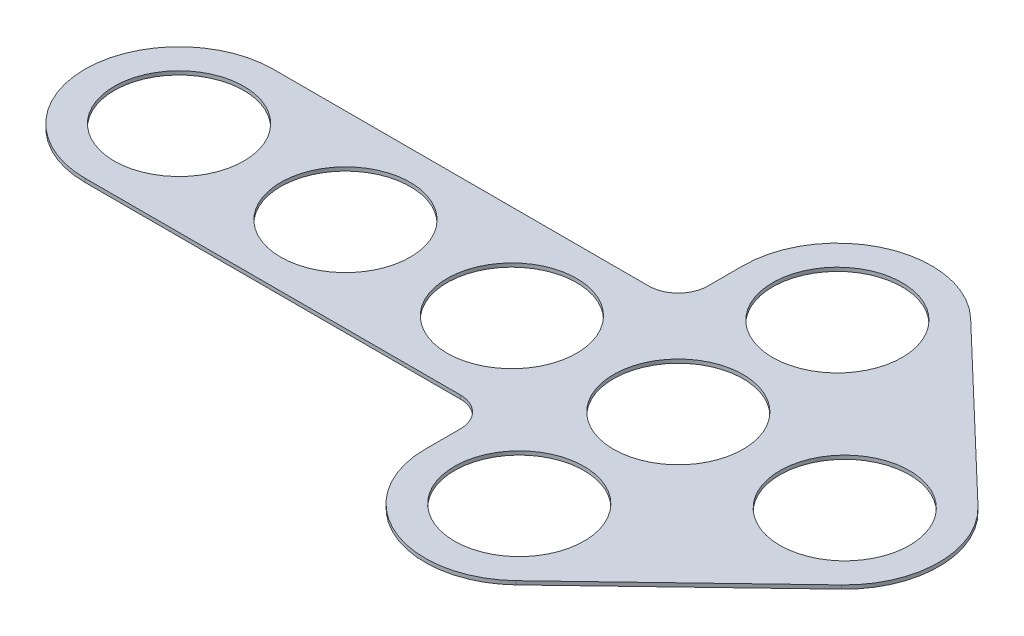
SolidWorks part; units mm, degrees
ref_plane "Front Plane" through (0, 0, 0) normal (0, 0, 1) x (1, 0, 0)
ref_plane "Top Plane" through (0, 0, 0) normal (0, 1, 0) x (1, 0, 0)
ref_plane "Right Plane" through (0, 0, 0) normal (1, 0, 0) x (0, 0, -1)
sketch "Sketch1" plane through (0, 0, 0) normal (0, 1, 0) x (1, 0, 0)
  line L0 (0, 228.6) -> (812.8, 228.6) construction
  line L1 (0, 0) -> (812.8, 0) construction
  line L2 (0, 0) -> (0, 457.2) construction
  line L3 (0, 457.2) -> (812.8, 457.2) construction
  line L4 (812.8, 0) -> (812.8, 457.2) construction
  line L5 (518.16, 228.6) -> (518.16, 365.76) construction
  line L6 (518.16, 228.6) -> (518.16, 91.44) construction
  line L8 (87.63, 309.88) -> (436.88, 309.88)
  line L9 (436.88, 309.88) -> (436.88, 365.76)
  line L11 (574.319, 424.5189) -> (717.829, 287.3589)
  line L12 (717.829, 169.8411) -> (574.319, 32.6811)
  line L14 (436.88, 91.44) -> (436.88, 147.32)
  line L15 (436.88, 147.32) -> (87.63, 147.32)
  circle A0 centre (87.63, 228.6) radius 55.88
  circle A1 centre (231.14, 228.6) radius 55.88
  circle A2 centre (374.65, 228.6) radius 55.88
  circle A3 centre (518.16, 228.6) radius 55.88
  circle A4 centre (661.67, 228.6) radius 55.88
  circle A5 centre (518.16, 365.76) radius 55.88
  circle A6 centre (518.16, 91.44) radius 55.88
  arc A7 (574.319, 424.5189) -> (436.88, 365.76) centre (518.16, 365.76) ccw
  arc A8 (717.829, 169.8411) -> (717.829, 287.3589) centre (661.67, 228.6) ccw
  arc A9 (436.88, 91.44) -> (574.319, 32.6811) centre (518.16, 91.44) ccw
  arc A12 (87.63, 309.88) -> (87.63, 147.32) centre (87.63, 228.6) ccw
  dimension "D3" = 111.76
  dimension "D4" = 31.75
  dimension "D5" = 31.75
  dimension "D6" = 31.75
  dimension "D7" = 31.75
  dimension "D8" = 31.75
  dimension "D9" = 25.4
  dimension "D10" = 25.4
  dimension "D15" = 162.56
  dimension "D12" = 162.56
  dimension "D11" = 162.56
  dimension "D16" = 162.56
  dimension "D1" = 457.2
  dimension "D2" = 812.8
extrude "Boss-Extrude1" add sketch "Sketch1" along normal blind 3.175
fillet "Fillet1" radius 25.4 2 edges at (436.88, 1.5875, -309.88) (436.88, 1.5875, -147.32)
